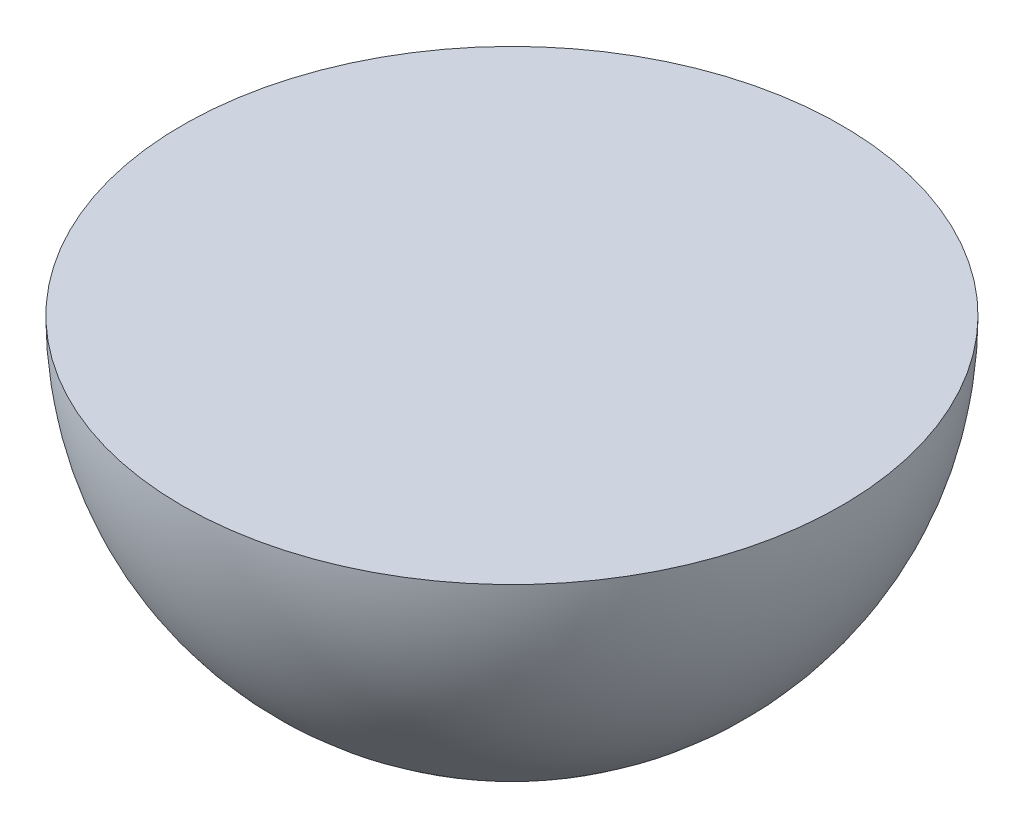
SolidWorks part; units mm, degrees
ref_plane "Front Plane" through (0, 0, 0) normal (0, 0, 1) x (1, 0, 0)
ref_plane "Top Plane" through (0, 0, 0) normal (0, 1, 0) x (1, 0, 0)
ref_plane "Right Plane" through (0, 0, 0) normal (1, 0, 0) x (0, 0, -1)
sketch "Sketch1" plane through (0, 0, 0) normal (1, 0, 0) x (0, 0, -1)
  line L0 (0, 92.9348) -> (0, -89.6739) construction
  line L1 (-325, 1.6304) -> (-425, 1.6304)
  line L2 (-325, 1.6304) -> (-325, -98.3696)
  line L3 (-325, 77.2319) -> (-325, -194.2194) construction
  arc A0 (-425, 1.6304) -> (-325, -98.3696) centre (-325, 1.6304) ccw
revolve "Revolve1" add sketch "Sketch1" angle 360 about L3
